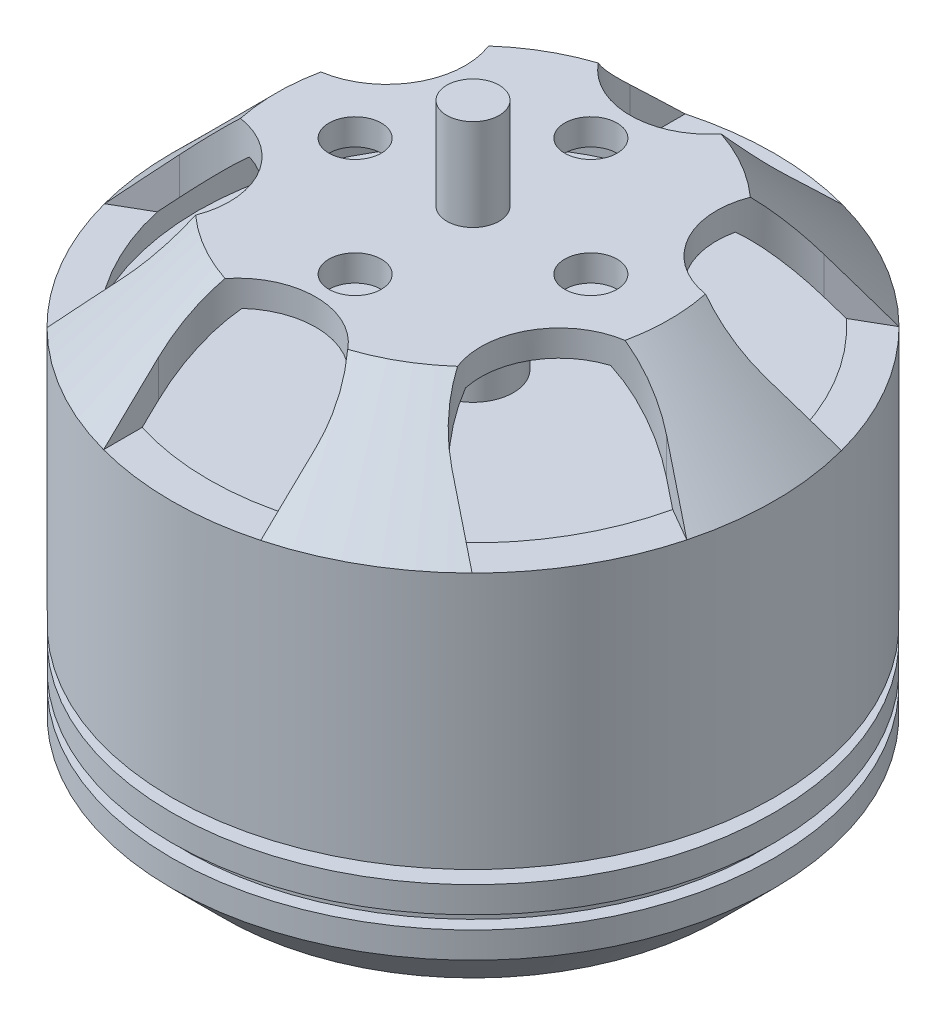
SolidWorks part; units mm, degrees
ref_plane "Front Plane" through (0, 0, 0) normal (0, 0, 1) x (1, 0, 0)
ref_plane "Top Plane" through (0, 0, 0) normal (0, 1, 0) x (1, 0, 0)
ref_plane "Right Plane" through (0, 0, 0) normal (1, 0, 0) x (0, 0, -1)
sketch "Sketch1" plane through (0, 0, 0) normal (0, 0, 1) x (1, 0, 0)
  line L1 (4.2566, 0.2623) -> (12.7566, 0.2623)
  line L2 (12.7566, 0.2623) -> (14.7566, 2.2623)
  line L3 (14.7566, 2.2623) -> (14.7566, 3.2623)
  line L4 (14.7566, 15.0623) -> (10.7566, 19.0623)
  line L5 (10.7566, 19.0623) -> (4.2566, 19.0623)
  line L6 (4.2566, 19.0623) -> (4.2566, 22.5623)
  line L7 (4.2566, 22.5623) -> (3.2566, 22.5623)
  line L9 (3.2566, -1.2377) -> (4.2566, -1.2377)
  line L10 (4.2566, -1.2377) -> (4.2566, 0.2623)
  line L11 (3.2566, 22.5623) -> (3.2566, -1.2377)
  line L19 (5.7954, 18.0623) -> (10.3424, 18.0623)
  line L20 (10.3424, 18.0623) -> (13.7566, 14.6481)
  line L24 (4.7954, 17.0623) -> (5.7954, 17.0623)
  line L25 (5.7954, 17.0623) -> (5.7954, 18.0623)
  line L26 (13.7566, 14.6481) -> (13.7566, 13.6632)
  line L27 (13.7566, 13.6632) -> (4.7954, 13.6632)
  line L28 (4.7954, 13.6632) -> (4.7954, 17.0623)
  line L29 (14.7566, 3.7623) -> (14.2566, 3.7623)
  line L30 (14.2566, 3.7623) -> (14.2566, 3.2623)
  line L31 (14.2566, 3.2623) -> (14.7566, 3.2623)
  line L32 (14.7566, 5.2623) -> (12.7566, 5.2623)
  line L33 (12.7566, 5.2623) -> (12.7566, 4.7623)
  line L34 (12.7566, 4.7623) -> (14.7566, 4.7623)
  line L35 (14.7566, 5.2623) -> (14.7566, 15.0623)
  line L36 (14.7566, 3.7623) -> (14.7566, 4.7623)
  dimension "D1" = 23.8
  dimension "D2" = 1
  dimension "D3" = 1
  dimension "D4" = 45
  dimension "D5" = 45
  dimension "D6" = 4
  dimension "D7" = 2
  dimension "D8" = 11.5
  dimension "D9" = 3.5
  dimension "D10" = 1.5
  dimension "D11" = 1
  dimension "D12" = 1
  dimension "D13" = 1
  dimension "D14" = 1
  dimension "D15" = 1
  dimension "D16" = 0.5
  dimension "D17" = 0.5
  dimension "D18" = 1
  dimension "D19" = 2
  dimension "D20" = 0.5
  dimension "D21" = 1
revolve "Revolve1" add sketch "Sketch1" angle 360 about L11
sketch "Sketch2" plane through (0, 19.0623, 0) normal (0, 1, 0) x (1, 0, 0)
  line L0 (3.2566, 0) -> (3.2566, 9) construction
  line L1 (0.2566, 9) -> (0.2566, 16.1262)
  line L2 (0.2566, 16.1262) -> (6.2566, 16.1262)
  line L3 (6.2566, 16.1262) -> (6.2566, 9)
  line L4 (-6.0376, 1.9019) -> (-12.2091, 5.465)
  line L5 (-9.2091, 10.6612) -> (-3.0376, 7.0981)
  line L6 (-12.2091, 5.465) -> (-9.2091, 10.6612)
  line L7 (-3.0376, -7.0981) -> (-9.2091, -10.6612)
  line L8 (-12.2091, -5.465) -> (-6.0376, -1.9019)
  line L9 (-9.2091, -10.6612) -> (-12.2091, -5.465)
  line L10 (6.2566, -9) -> (6.2566, -16.1262)
  line L11 (0.2566, -16.1262) -> (0.2566, -9)
  line L12 (6.2566, -16.1262) -> (0.2566, -16.1262)
  line L13 (12.5508, -1.9019) -> (18.7223, -5.465)
  line L14 (15.7223, -10.6612) -> (9.5508, -7.0981)
  line L15 (18.7223, -5.465) -> (15.7223, -10.6612)
  line L16 (9.5508, 7.0981) -> (15.7223, 10.6612)
  line L17 (18.7223, 5.465) -> (12.5508, 1.9019)
  line L18 (15.7223, 10.6612) -> (18.7223, 5.465)
  circle A0 centre (3.2566, 0) radius 4.5 construction
  circle A1 centre (3.2566, 0) radius 9.2189 construction
  circle A2 centre (3.2566, -4.5) radius 1
  circle A3 centre (-1.2434, 0) radius 1
  circle A4 centre (3.2566, 4.5) radius 1
  circle A5 centre (7.7566, 0) radius 1
  arc A6 (0.2566, 9) -> (6.2566, 9) centre (3.2566, 9) ccw
  arc A7 (-6.0376, 1.9019) -> (-3.0376, 7.0981) centre (-4.5376, 4.5) ccw
  arc A8 (-3.0376, -7.0981) -> (-6.0376, -1.9019) centre (-4.5376, -4.5) ccw
  arc A9 (6.2566, -9) -> (0.2566, -9) centre (3.2566, -9) ccw
  arc A10 (12.5508, -1.9019) -> (9.5508, -7.0981) centre (11.0508, -4.5) ccw
  arc A11 (9.5508, 7.0981) -> (12.5508, 1.9019) centre (11.0508, 4.5) ccw
  point P16 (3.2566, 0)
  point P46 (3.2566, 0)
  dimension "D1" = 9
  dimension "D3" = 2
  dimension "D5" = 6
  dimension "D2" = 9
  dimension "D4" = 4
  dimension "D6" = 6
extrude "Cut-Extrude1" cut sketch "Sketch2" against normal blind 4
sketch "Sketch3" plane through (0, 0.2623, 0) normal (0, -1, 0) x (1, 0, 0)
  circle A0 centre (3.2566, 0) radius 6 construction
  circle A1 centre (3.2566, 0) radius 8 construction
  circle A2 centre (3.2566, 6) radius 1
  circle A3 centre (3.2566, -6) radius 1
  circle A4 centre (11.2566, 0) radius 1
  circle A5 centre (-4.7434, 0) radius 1
  dimension "D1" = 12
  dimension "D2" = 16
  dimension "D3" = 2
extrude "Cut-Extrude2" cut sketch "Sketch3" against normal blind 3
